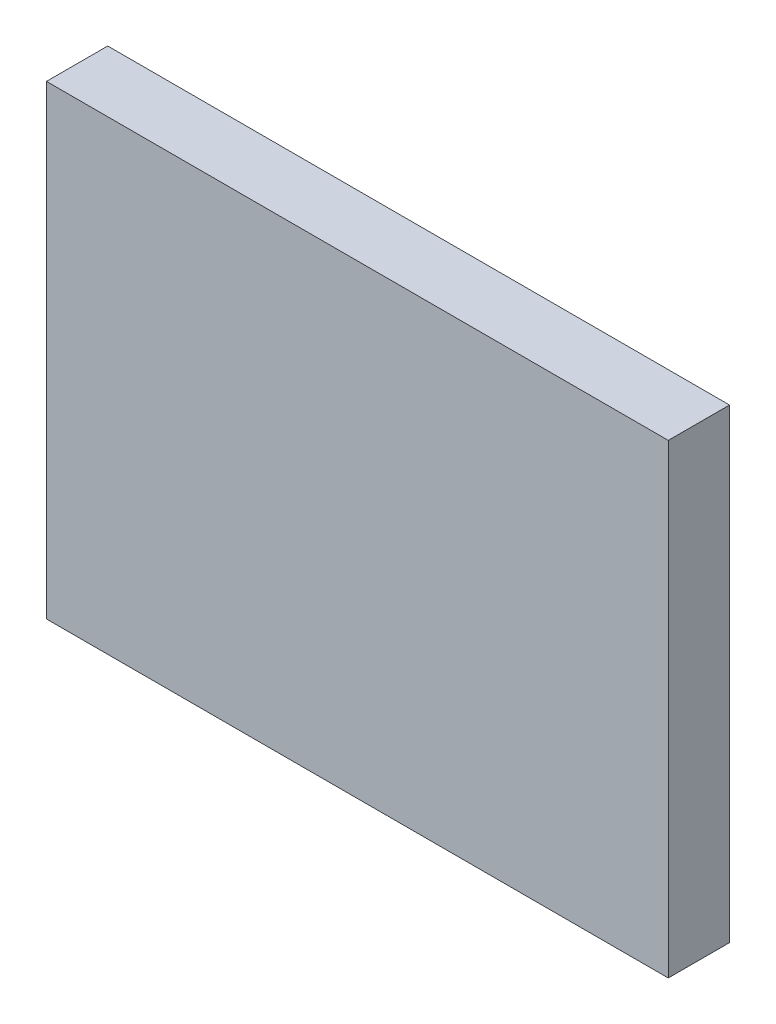
SolidWorks part; units mm, degrees
ref_plane "Plan de face" through (0, 0, 0) normal (0, 0, 1) x (1, 0, 0)
ref_plane "Plan de dessus" through (0, 0, 0) normal (0, 1, 0) x (1, 0, 0)
ref_plane "Plan de droite" through (0, 0, 0) normal (1, 0, 0) x (0, 0, -1)
sketch "Esquisse1" plane through (0, 0, 0) normal (0, 0, 1) x (1, 0, 0)
  line L1 (-10.1853, 12.9478) -> (10.1147, 12.9478)
  line L2 (-10.1853, 12.9478) -> (-10.1853, -2.2522)
  line L3 (-10.1853, -2.2522) -> (10.1147, -2.2522)
  line L4 (10.1147, 12.9478) -> (10.1147, -2.2522)
  dimension "D1" = 20.3
  dimension "D2" = 15.2
extrude "Boss.-Extru.1" add sketch "Esquisse1" along normal blind 2
